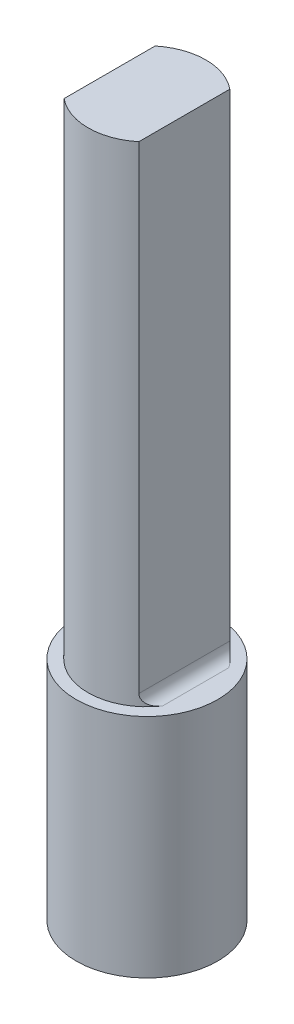
SolidWorks part; units mm, degrees
ref_plane "Front" through (0, 0, 0) normal (0, 0, 1) x (1, 0, 0)
ref_plane "Top" through (0, 0, 0) normal (0, 1, 0) x (1, 0, 0)
ref_plane "Right" through (0, 0, 0) normal (1, 0, 0) x (0, 0, -1)
sketch "Sketch1" plane through (0, 0, 0) normal (0, 1, 0) x (1, 0, 0)
  circle A0 centre (0, 0) radius 3.125
  dimension "D1" = 6.25
extrude "Boss-Extrude1" add sketch "Sketch1" along normal mid plane 10
sketch "Sketch2" plane through (0, 5, 0) normal (0, 1, 0) x (1, 0, 0)
  line L0 (-1.65, -2.0094) -> (-1.65, 2.0094)
  line L1 (1.65, 2.0094) -> (1.65, -2.0094)
  line L2 (-1.65, 0) -> (1.65, 0) construction
  arc A0 (-1.65, -2.0094) -> (1.65, -2.0094) centre (0, 0) ccw
  arc A1 (1.65, 2.0094) -> (-1.65, 2.0094) centre (0, 0) ccw
  point P10 (0, 0)
  dimension "D1" = 5.2
  dimension "D2" = 3.3
extrude "Boss-Extrude2" add sketch "Sketch2" along normal blind 21.6
fillet "Fillet1" radius 0.5 2 edges at (1.65, 5, 0) (-1.65, 5, 0)
